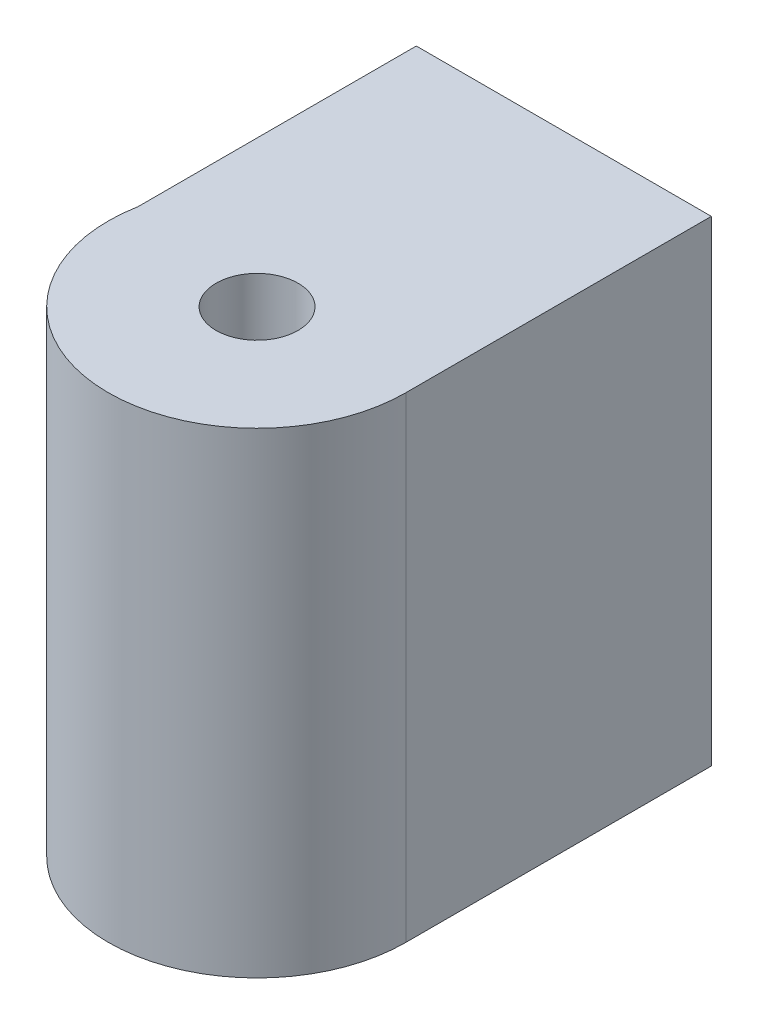
SolidWorks part; units mm, degrees
ref_plane "Front Plane" through (0, 0, 0) normal (0, 0, 1) x (1, 0, 0)
ref_plane "Top Plane" through (0, 0, 0) normal (0, 1, 0) x (1, 0, 0)
ref_plane "Right Plane" through (0, 0, 0) normal (1, 0, 0) x (0, 0, -1)
sketch "Sketch2" plane through (0, -2111.3899, 0) normal (0, 1, 0) x (1, 0, 0)
  circle A1 centre (-53.694, 163.8403) radius 12.7
extrude "Boss-Extrude6" add sketch "Sketch2" along normal blind 40.64
sketch "Sketch3" plane through (0, -2070.7499, 0) normal (0, 1, 0) x (1, 0, 0)
  circle A0 centre (-53.694, 163.8403) radius 3.5
  dimension "D1" = 7
extrude "Cut-Extrude1" cut sketch "Sketch3" against normal up to surface (40.64 mm away) up to face at (-66.394, -2111.3899, -163.8403)
sketch "Sketch4" plane through (0, -2111.3899, 0) normal (0, -1, 0) x (1, 0, 0)
  circle A0 centre (-61.9429, -159.0778) radius 1.778
  circle A2 centre (-53.694, -173.3653) radius 1.778
  circle A3 centre (-45.4451, -159.0778) radius 1.778
extrude "Cut-Extrude2" cut sketch "Sketch4" against normal blind 6
sketch "Sketch7" plane through (0, -2111.3899, 0) normal (0, -1, 0) x (1, 0, 0)
  line L9 (-40.994, -163.8403) -> (-40.994, -182.6343)
  line L10 (-40.994, -182.6343) -> (-66.1797, -182.6343)
  line L11 (-66.1797, -166.1636) -> (-66.1797, -182.6343)
  circle A0 centre (-53.694, -163.8403) radius 12.7 construction
  arc A1 (-66.1797, -166.1636) -> (-40.994, -163.8403) centre (-53.694, -163.8403) ccw
extrude "Boss-Extrude8" add sketch "Sketch7" against normal blind 10
sketch "Sketch8" plane through (0, 0, -182.6343) normal (0, 0, -1) x (-1, 0, 0)
  line L0 (40.994, -2101.3899) -> (40.994, -2111.3899) construction
  line L1 (40.994, -2101.3899) -> (66.1797, -2101.3899)
  line L2 (40.994, -2101.3899) -> (40.994, -2111.3899)
  line L3 (40.994, -2111.3899) -> (66.1797, -2111.3899)
  line L4 (66.1797, -2101.3899) -> (66.1797, -2111.3899)
  line L5 (66.1797, -2101.3899) -> (40.994, -2101.3899) construction
  line L6 (66.1797, -2111.3899) -> (40.994, -2111.3899) construction
  line L7 (66.1797, -2101.3899) -> (66.1797, -2111.3899) construction
extrude "Boss-Extrude9" add sketch "Sketch8" along normal up to surface (7.2848 mm away)
sketch "Sketch9" plane through (0, -2070.7499, 0) normal (0, 1, 0) x (1, 0, 0)
  line L0 (-40.994, 189.9191) -> (-40.994, 163.8403) construction
  line L2 (-66.1797, 163.8403) -> (-66.1797, 189.9191)
  line L3 (-66.1797, 189.9191) -> (-40.994, 189.9191)
  line L4 (-40.994, 163.8403) -> (-40.994, 189.9191)
  line L5 (-66.1797, 166.1636) -> (-66.1797, 189.9191) construction
  arc A0 (-40.994, 163.8403) -> (-66.1797, 163.8403) centre (-53.5868, 163.8403) ccw
extrude "Boss-Extrude10" add sketch "Sketch9" against normal up to surface (30.64 mm away) up to face at (-53.322, -2101.3899, -180.3317)
hole_wizard "CSK for M3 Flat Head Machine Screw1" positions "Sketch14" profile "Sketch15" countersink size "M3" standard "ANSI Metric"
sketch "Sketch14" plane through (0, 0, -189.9191) normal (0, 0, -1) x (-1, 0, 0)
  point P10 (53.5868, -2075.7499)
  point P12 (62.6264, -2075.7499)
  point P14 (44.5473, -2075.7499)
sketch "Sketch15" plane through (-53.5868, -2075.7499, -189.9191) normal (1, 0, 0) x (0, 1, 0)
  line L0 (0, 0) -> (0, 10)
  line L1 (0, 10) -> (1.7, 8.9785)
  line L2 (1.7, 8.9785) -> (1.7, 1.45)
  line L3 (1.7, 1.45) -> (3.15, 0)
  line L5 (3.15, 0) -> (0, 0)
  line L6 (-1.7, 1.45) -> (-3.15, 0) construction
  line L10 (0, 10) -> (-1.7, 8.9785) construction
  line L11 (0, -6.35) -> (0, 107.95) construction
  dimension "Hole Dia." = 3.4
  dimension "Hole Depth" = 10
  dimension "Near C'Sink Dia." = 6.3
  dimension "Near C'Sink Angle" = 90
  dimension "Drill Angle" = 118
ref_plane "Plane1" through (0, -2091.0699, 0) normal (0, 1, 0) x (1, 0, 0)
mirror "Mirror1" about plane through (0, -2091.0699, 0) normal (0, 1, 0) of "CSK for M3 Flat Head Machine Screw1"
